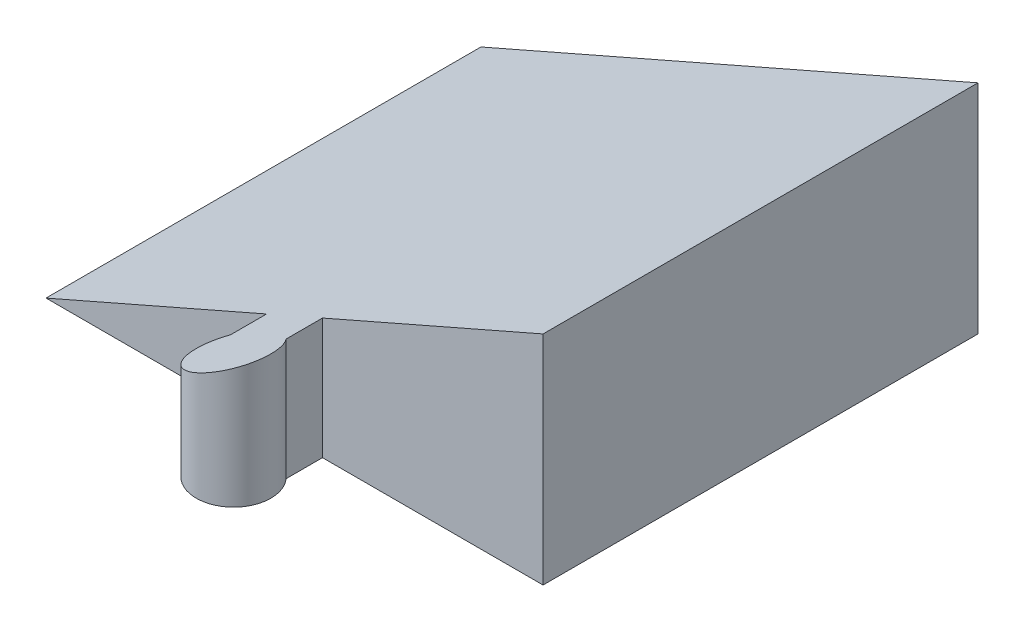
SolidWorks part; units mm, degrees
ref_plane "Front Plane" through (0, 0, 0) normal (0, 0, 1) x (1, 0, 0)
ref_plane "Top Plane" through (0, 0, 0) normal (0, 1, 0) x (1, 0, 0)
ref_plane "Right Plane" through (0, 0, 0) normal (1, 0, 0) x (0, 0, -1)
sketch "Esboço1" plane through (0, 0, 0) normal (0, 0, 1) x (1, 0, 0)
  line L0 (-46.1667, -15.6528) -> (33.8333, 19.3472)
  line L3 (-46.1667, -15.6528) -> (33.8333, -15.6528)
  line L4 (33.8333, 19.3472) -> (33.8333, -15.6528)
  dimension "D1" = 35
  dimension "D2" = 80
extrude "Ressalto-extrusão1" add sketch "Esboço1" along normal blind 70
sketch "Esboço2" plane through (0, -15.6528, 0) normal (0, -1, 0) x (1, 0, 0)
  line L0 (33.8333, 35) -> (-46.1667, 35) construction
  line L1 (33.8333, 70) -> (33.8333, 0) construction
  line L2 (-46.1667, 70) -> (-46.1667, 0) construction
  line L3 (-6.1667, 0) -> (-6.1667, 3.5) construction
  line L4 (-46.1667, 0) -> (33.8333, 0) construction
  line L5 (-46.1667, 70) -> (33.8333, 70) construction
  line L6 (-6.1667, 10) -> (-6.1667, 70) construction
  line L7 (-11.1667, 0) -> (-1.1667, 0)
  line L8 (-11.1667, 0) -> (-11.1667, 5.8467)
  line L10 (-1.1667, 0) -> (-1.1667, 5.8467)
  arc A0 (-1.1667, 5.8467) -> (-11.1667, 5.8467) centre (-6.1667, 10) ccw
  point P16 (-6.1667, 0)
  point P19 (0, 0)
  dimension "D3" = 13
  dimension "D1" = 5
sketch "Esboço3" plane through (0, -15.6528, 0) normal (0, -1, 0) x (1, 0, 0)
  line L0 (-6.1667, 70) -> (-6.1667, 73.5) construction
  line L1 (-10.6667, 70) -> (-1.6667, 70)
  line L2 (-10.6667, 70) -> (-10.6667, 75.8467)
  line L3 (-1.6667, 70) -> (-1.6667, 75.8467)
  arc A0 (-1.6667, 75.8467) -> (-10.6667, 75.8467) centre (-6.1667, 79.8153) ccw
  point P4 (-6.1667, 70)
  point P8 (0, 0)
  dimension "D2" = 6
  dimension "D1" = 4.5
extrude "Ressalto-extrusão2" add sketch "Esboço3" against normal up to surface (15.5313 mm away)
